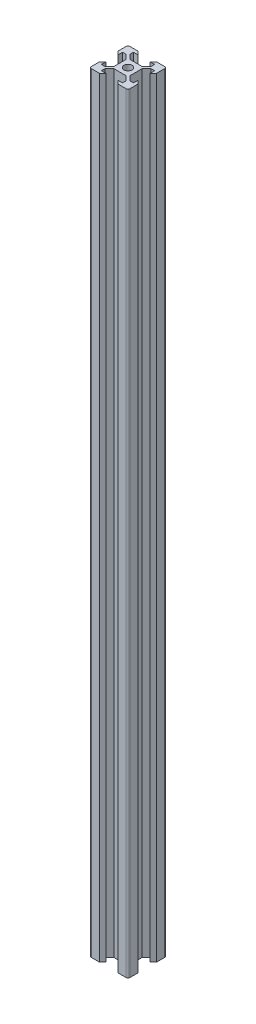
SolidWorks part; units mm, degrees
material "1060 Alloy"
ref_plane "Front Plane" through (0, 0, 0) normal (0, 0, 1) x (1, 0, 0)
ref_plane "Top Plane" through (0, 0, 0) normal (0, 1, 0) x (1, 0, 0)
ref_plane "Right Plane" through (0, 0, 0) normal (1, 0, 0) x (0, 0, -1)
ref_plane "End Plane" through (0, 400, 0) normal (0, 1, 0) x (1, 0, 0)
sketch "MasterLayoutSketch" plane through (0, 0, 0) normal (0, 1, 0) x (1, 0, 0)
  line L0 (-8.325, 3.1) -> (-8.325, 5.5)
  line L1 (-10, -10) -> (10, -10) construction
  line L2 (-10, -10) -> (-10, 10) construction
  line L3 (-10, 10) -> (10, 10) construction
  line L4 (10, -10) -> (10, 10) construction
  line L5 (-10, -10) -> (10, 10) construction
  line L6 (-10, 10) -> (10, -10) construction
  line L7 (-4.775, 10) -> (-3.1, 8.325)
  line L10 (-8.325, 5.5) -> (-6.5607, 5.5)
  line L11 (-10, 4.775) -> (-8.325, 3.1)
  line L12 (-5.5, 8.325) -> (-5.5, 6.5607)
  line L13 (-3.1, 8.325) -> (-5.5, 8.325)
  line L14 (-10, 10) -> (-10, 4.775)
  line L19 (3.1, 8.325) -> (5.5, 8.325)
  line L20 (10, 4.775) -> (8.325, 3.1)
  line L21 (-10, 10) -> (-4.775, 10)
  line L22 (-6.5607, 5.5) -> (-4.1607, 3.1)
  line L23 (-5.5, 6.5607) -> (-3.1, 4.1607)
  line L24 (5.5, 8.325) -> (5.5, 6.5607)
  line L25 (4.775, 10) -> (3.1, 8.325)
  line L26 (8.325, 5.5) -> (6.5607, 5.5)
  line L27 (8.325, 3.1) -> (8.325, 5.5)
  line L28 (10, 10) -> (4.775, 10)
  line L29 (10, 10) -> (10, 4.775)
  line L30 (5.5, 6.5607) -> (3.1, 4.1607)
  line L31 (6.5607, 5.5) -> (4.1607, 3.1)
  line L32 (8.325, -3.1) -> (8.325, -5.5)
  line L33 (4.775, -10) -> (3.1, -8.325)
  line L34 (8.325, -5.5) -> (6.5607, -5.5)
  line L35 (10, -4.775) -> (8.325, -3.1)
  line L36 (5.5, -8.325) -> (5.5, -6.5607)
  line L37 (3.1, -8.325) -> (5.5, -8.325)
  line L38 (10, -10) -> (10, -4.775)
  line L39 (10, -10) -> (4.775, -10)
  line L40 (6.5607, -5.5) -> (4.1607, -3.1)
  line L41 (5.5, -6.5607) -> (3.1, -4.1607)
  line L42 (-3.1, -8.325) -> (-5.5, -8.325)
  line L43 (-10, -4.775) -> (-8.325, -3.1)
  line L44 (-5.5, -8.325) -> (-5.5, -6.5607)
  line L45 (-4.775, -10) -> (-3.1, -8.325)
  line L46 (-8.325, -5.5) -> (-6.5607, -5.5)
  line L47 (-8.325, -3.1) -> (-8.325, -5.5)
  line L48 (-10, -10) -> (-4.775, -10)
  line L49 (-10, -10) -> (-10, -4.775)
  line L50 (-5.5, -6.5607) -> (-3.1, -4.1607)
  line L51 (-6.5607, -5.5) -> (-4.1607, -3.1)
  line L52 (-4.1607, 3.1) -> (-4.1607, -3.1)
  line L53 (-3.1, -4.1607) -> (3.1, -4.1607)
  line L54 (4.1607, -3.1) -> (4.1607, 3.1)
  line L55 (-3.1, 4.1607) -> (3.1, 4.1607)
  circle A0 centre (0, 0) radius 2.1
  point P0 (0, 0)
  point P9 (0, 0)
  dimension "D6" = 4.2
  dimension "D1" = 20
  dimension "D2" = 4
  dimension "D3" = 11
  dimension "D4" = 9.55
  dimension "D5" = 6.2
  dimension "D7" = 1.5
extrude "Main Extrusion" add sketch "MasterLayoutSketch" along normal up to surface (400 mm away) up to plane "End Plane"
fillet "Edge Fillets" radius 1 4 edges at (10, 200, -10) (10, 200, 10) (-10, 200, 10) (-10, 200, -10)
